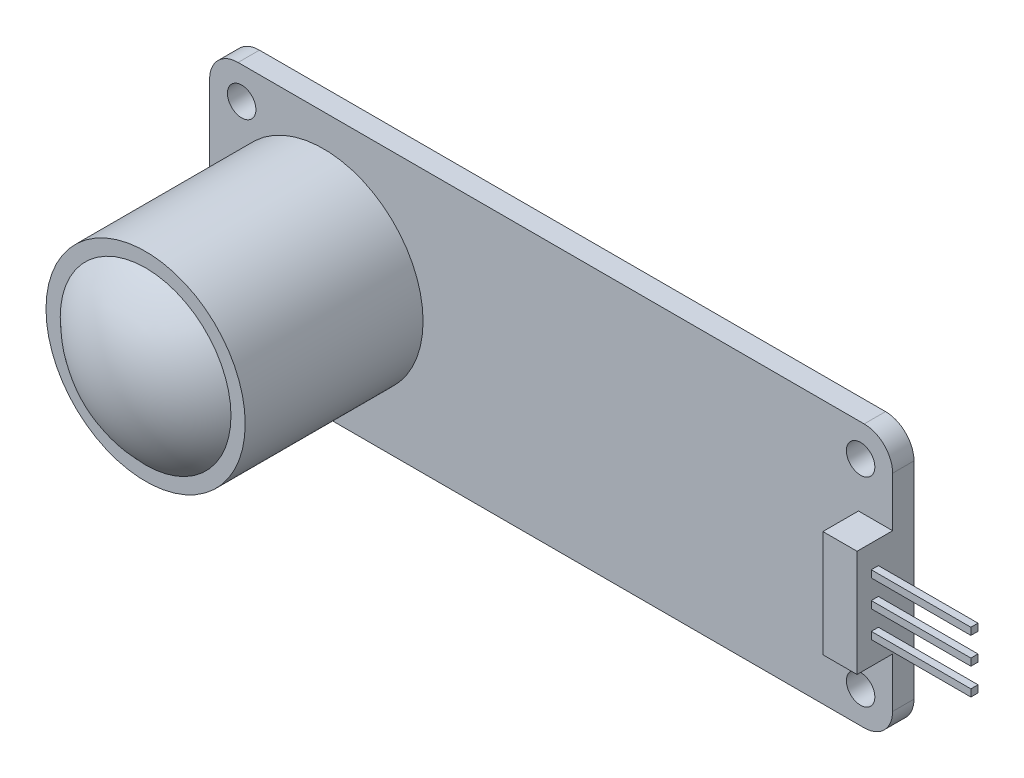
SolidWorks part; units mm, degrees
ref_plane "Front Plane" through (0, 0, 0) normal (0, 0, 1) x (1, 0, 0)
ref_plane "Top Plane" through (0, 0, 0) normal (0, 1, 0) x (1, 0, 0)
ref_plane "Right Plane" through (0, 0, 0) normal (1, 0, 0) x (0, 0, -1)
sketch "Sketch1" plane through (0, 0, 0) normal (0, 0, 1) x (1, 0, 0)
  line L1 (-24, -9.25) -> (24, -9.25)
  line L2 (-24, -9.25) -> (-24, 9.25)
  line L3 (-24, 9.25) -> (24, 9.25)
  line L4 (24, -9.25) -> (24, 9.25)
  line L5 (-24, -9.25) -> (24, 9.25) construction
  line L6 (-24, 9.25) -> (24, -9.25) construction
  line L7 (-21.75, -7) -> (21.75, -7) construction
  line L8 (-21.75, -7) -> (-21.75, 7) construction
  line L9 (-21.75, 7) -> (21.75, 7) construction
  line L10 (21.75, -7) -> (21.75, 7) construction
  line L11 (-21.75, -7) -> (21.75, 7) construction
  line L12 (-21.75, 7) -> (21.75, -7) construction
  circle A0 centre (-21.75, 7) radius 1
  circle A1 centre (21.75, 7) radius 1
  circle A2 centre (21.75, -7) radius 1
  circle A3 centre (-21.75, -7) radius 1
  point P0 (0, 0)
  point P6 (0, 0)
  dimension "D1" = 48
  dimension "D2" = 18.5
  dimension "D3" = 43.5
  dimension "D4" = 14
extrude "Boss-Extrude1" add sketch "Sketch1" along normal blind 1.5
fillet "Fillet1" radius 2 4 edges at (-24, -9.25, 0.75) (-24, 9.25, 0.75) (24, -9.25, 0.75) (24, 9.25, 0.75)
sketch "Sketch2" plane through (0, 0, 1.5) normal (0, 0, 1) x (1, 0, 0)
  line L0 (-24, 7.25) -> (-24, -7.25) construction
  line L1 (-22, -9.25) -> (22, -9.25) construction
  circle A0 centre (-16, 0) radius 7
  point P2 (-16.1873, 0)
  point P5 (0, 0)
  dimension "D1" = 8
  dimension "D2" = 9.25
extrude "Boss-Extrude2" add sketch "Sketch2" along normal blind 12.5
ref_plane "Plane1" through (0, 0, 0) normal (0, -1, 0) x (-1, 0, 0)
sketch "Sketch3" plane through (0, 0, 0) normal (0, -1, 0) x (-1, 0, 0)
  line L0 (9, -14) -> (23, -14) construction
  line L1 (9, -14) -> (11.1266, -14) construction
  line L2 (16, -1014) -> (16, -14) construction
  line L3 (16, -14) -> (16, -16.5)
  line L4 (16, -14) -> (23, -14) construction
  line L5 (22, -14) -> (16, -14)
  line L6 (16, -4.5) -> (16, 1001.9406) construction
  arc A0 (16, -16.5) -> (22, -14) centre (16, -8.05) ccw
  point P3 (16, -14)
  point P7 (16, -16.5)
  point P8 (16, -14)
  dimension "D1" = 2.5
  dimension "D2" = 1
revolve "Revolve3" add sketch "Sketch3" angle 360 about L2
sketch "Sketch5" plane through (0, 0, 1.5) normal (0, 0, 1) x (1, 0, 0)
  line L0 (24, -7.25) -> (24, 7.25) construction
  line L1 (24, -3.75) -> (21.6, -3.75)
  line L2 (24, -3.75) -> (24, 3.75)
  line L3 (24, 3.75) -> (21.6, 3.75)
  line L4 (21.6, -3.75) -> (21.6, 3.75)
  line L5 (-0.825, 0) -> (0.825, 0) construction
  point P6 (24, 0)
  dimension "D1" = 7.5
  dimension "D2" = 2.4
extrude "Boss-Extrude3" add sketch "Sketch5" along normal blind 2.5
sketch "Sketch6" plane through (24, 0, 0) normal (1, 0, 0) x (0, 0, -1)
  line L0 (-2.75, 3.75) -> (-2.75, -3.75) construction
  line L1 (-4, 3.75) -> (-1.5, 3.75) construction
  line L2 (-4, -3.75) -> (-1.5, -3.75) construction
  line L3 (-4, 0) -> (0, 0) construction
  line L4 (-4, -3.75) -> (-4, 3.75) construction
  line L5 (-4, 0) -> (-4, 3.75) construction
  line L6 (-4, 0) -> (-4, -3.75) construction
  line L7 (-4, 1.875) -> (-2.75, 1.875) construction
  line L8 (-4, -1.875) -> (-2.75, -1.875) construction
  line L10 (-3, 1.625) -> (-2.5, 1.625)
  line L11 (-3, 1.625) -> (-3, 2.125)
  line L12 (-3, 2.125) -> (-2.5, 2.125)
  line L13 (-2.5, 1.625) -> (-2.5, 2.125)
  line L14 (-3, 1.625) -> (-2.5, 2.125) construction
  line L15 (-3, 2.125) -> (-2.5, 1.625) construction
  line L16 (-3, -0.25) -> (-2.5, -0.25)
  line L17 (-3, -0.25) -> (-3, 0.25)
  line L18 (-3, 0.25) -> (-2.5, 0.25)
  line L19 (-2.5, -0.25) -> (-2.5, 0.25)
  line L20 (-3, -0.25) -> (-2.5, 0.25) construction
  line L21 (-3, 0.25) -> (-2.5, -0.25) construction
  line L22 (-3, -2.125) -> (-2.5, -2.125)
  line L23 (-3, -2.125) -> (-3, -1.625)
  line L24 (-3, -1.625) -> (-2.5, -1.625)
  line L25 (-2.5, -2.125) -> (-2.5, -1.625)
  line L26 (-3, -2.125) -> (-2.5, -1.625) construction
  line L27 (-3, -1.625) -> (-2.5, -2.125) construction
  point P23 (-2.75, 0)
  dimension "D1" = 0.5
  dimension "D2" = 0.5
  dimension "D3" = 0.5
  dimension "D4" = 0.5
extrude "Boss-Extrude4" add sketch "Sketch6" along normal blind 7
